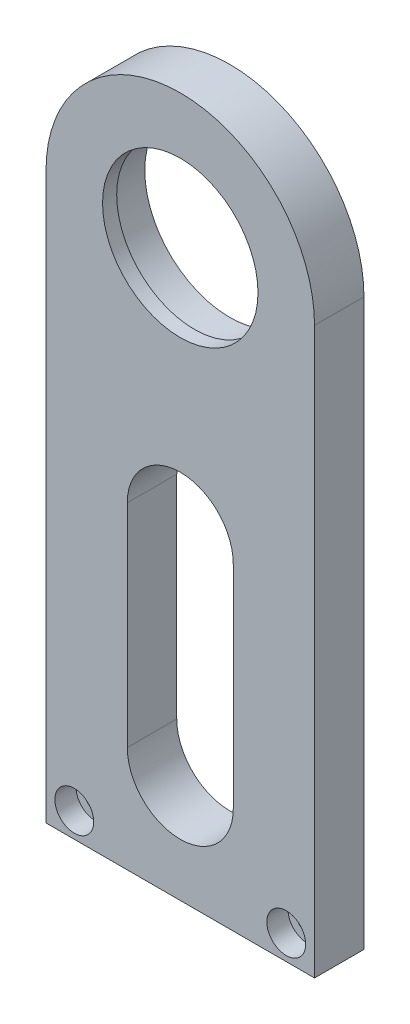
SolidWorks part; units mm, degrees
material "6061 合金"
ref_plane "前视基准面" through (0, 0, 0) normal (0, 0, 1) x (1, 0, 0)
ref_plane "上视基准面" through (0, 0, 0) normal (0, 1, 0) x (1, 0, 0)
ref_plane "右视基准面" through (0, 0, 0) normal (1, 0, 0) x (0, 0, -1)
sketch "草图1" plane through (0, 0, 0) normal (0, 0, 1) x (1, 0, 0)
  line L0 (0, 0) -> (0, 80) construction
  line L1 (-19, 0) -> (19, 0)
  line L2 (19, 0) -> (19, 7)
  line L3 (0, 45) -> (0, 15) construction
  line L4 (-19, 7) -> (-19, 0)
  line L5 (-19, 7) -> (-19, 80)
  line L6 (19, 7) -> (19, 80)
  line L7 (7.5, 45) -> (7.5, 15)
  line L8 (-7.5, 45) -> (-7.5, 15)
  circle A0 centre (0, 80) radius 11 construction
  circle A1 centre (0, 80) radius 19
  circle A2 centre (0, 80) radius 11
  circle A3 centre (15, 3.5) radius 1.55
  arc A4 (7.5, 45) -> (-7.5, 45) centre (0, 45) ccw
  arc A5 (-7.5, 15) -> (7.5, 15) centre (0, 15) ccw
  circle A6 centre (-15, 3.5) radius 1.55
  point P16 (0, 30)
  dimension "D1" = 22
  dimension "D3" = 80
  dimension "D4" = 35
  dimension "D5" = 7.5
  dimension "D6" = 15
  dimension "D7" = 3.1
  dimension "D8" = 3.5
  dimension "D9" = 4
  dimension "D2" = 38
extrude "凸台-拉伸1" add sketch "草图1" along normal blind 7
sketch "Sketch1" plane through (0, 0, 7) normal (0, 0, 1) x (1, 0, 0)
  line L0 (0, 0) -> (0, -20.1989) construction
  line L1 (-19, 0) -> (19, 0) construction
  circle A0 centre (15, 3.5) radius 2.75
  circle A1 centre (-15, 3.5) radius 2.75
  dimension "D1" = 5.5
extrude "Cut-Extrude1" cut sketch "Sketch1" against normal blind 3
sketch "Sketch2" plane through (0, 0, 0) normal (0, 0, -1) x (-1, 0, 0)
  circle A0 centre (0, 80) radius 12.025
  dimension "D1" = 24.05
extrude "Cut-Extrude2" cut sketch "Sketch2" against normal blind 5
